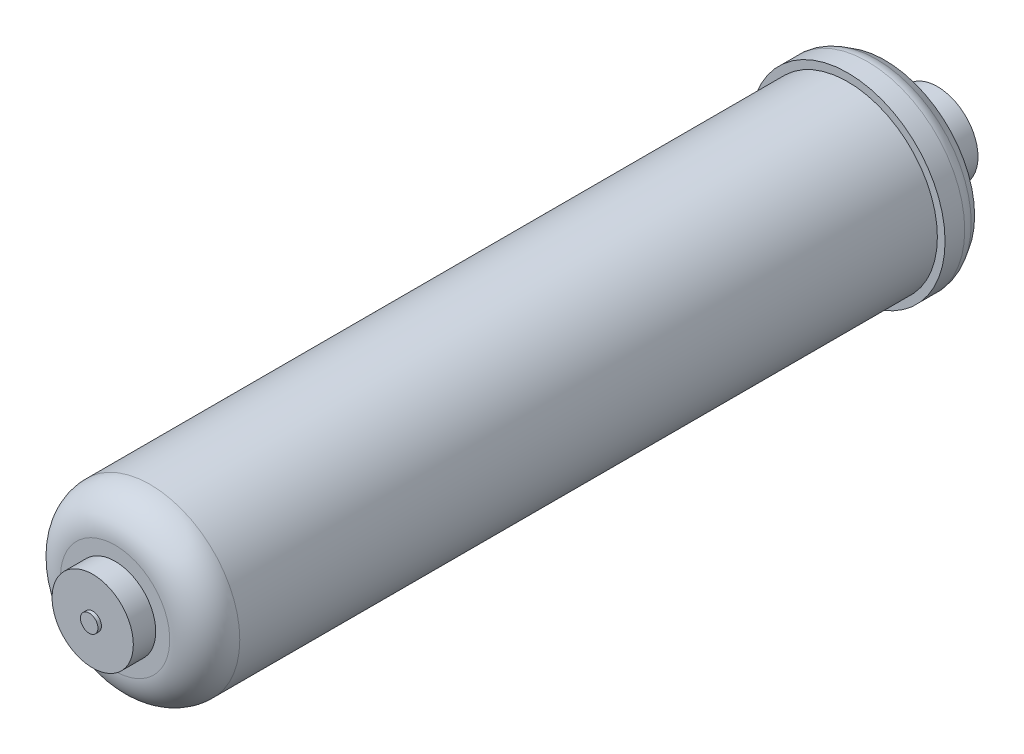
SolidWorks part; units mm, degrees
ref_plane "Front Plane" through (0, 0, 0) normal (0, 0, 1) x (1, 0, 0)
ref_plane "Top Plane" through (0, 0, 0) normal (0, 1, 0) x (1, 0, 0)
ref_plane "Right Plane" through (0, 0, 0) normal (1, 0, 0) x (0, 0, -1)
sketch "Sketch1" plane through (0, 0, 0) normal (1, 0, 0) x (0, 0, -1)
  line L0 (0, 0) -> (394.1281, 0) construction
  line L1 (0, 0) -> (0, 3.175)
  line L2 (0, 3.175) -> (1.27, 3.175)
  line L3 (1.27, 3.175) -> (1.27, 14.732)
  line L4 (1.27, 14.732) -> (9.398, 14.732)
  line L5 (9.398, 14.732) -> (9.398, 32.512)
  line L6 (9.398, 32.512) -> (275.082, 32.512)
  line L7 (275.082, 32.512) -> (275.082, 35.306)
  line L8 (275.082, 35.306) -> (283.972, 35.306)
  line L9 (283.972, 35.306) -> (288.544, 32.5551)
  line L10 (288.544, 32.5551) -> (299.466, 14.732)
  line L11 (299.466, 14.732) -> (307.594, 14.732)
  line L12 (307.594, 14.732) -> (307.594, 3.175)
  line L13 (307.594, 3.175) -> (308.864, 3.175)
  line L14 (308.864, 3.175) -> (308.864, 0)
  line L15 (0, 0) -> (308.864, 0)
  point P16 (110.7666, 0)
  point P18 (303.53, 14.732)
  point P19 (103.9167, 0)
  point P20 (84.8316, 32.512)
  point P21 (394.1281, 0)
  point P22 (290.7792, 29.97)
  point P23 (288.544, 32.051)
  dimension "D1" = 1.27
  dimension "D2" = 6.35
  dimension "D3" = 8.128
  dimension "D4" = 65.024
  dimension "D5" = 70.612
  dimension "D6" = 4.572
  dimension "D7" = 10.922
  dimension "D8" = 273.812
  dimension "D9" = 306.324
  dimension "D10" = 29.464
  dimension "D11" = 29.464
  dimension "D12" = 121.5
revolve "Revolve1" add sketch "Sketch1" angle 360 about L0
fillet "Fillet1" radius 12.7 1 edges at (32.512, 0, -9.398)
fillet "Fillet2" radius 6.35 1 edges at (35.306, 0, -283.972)
